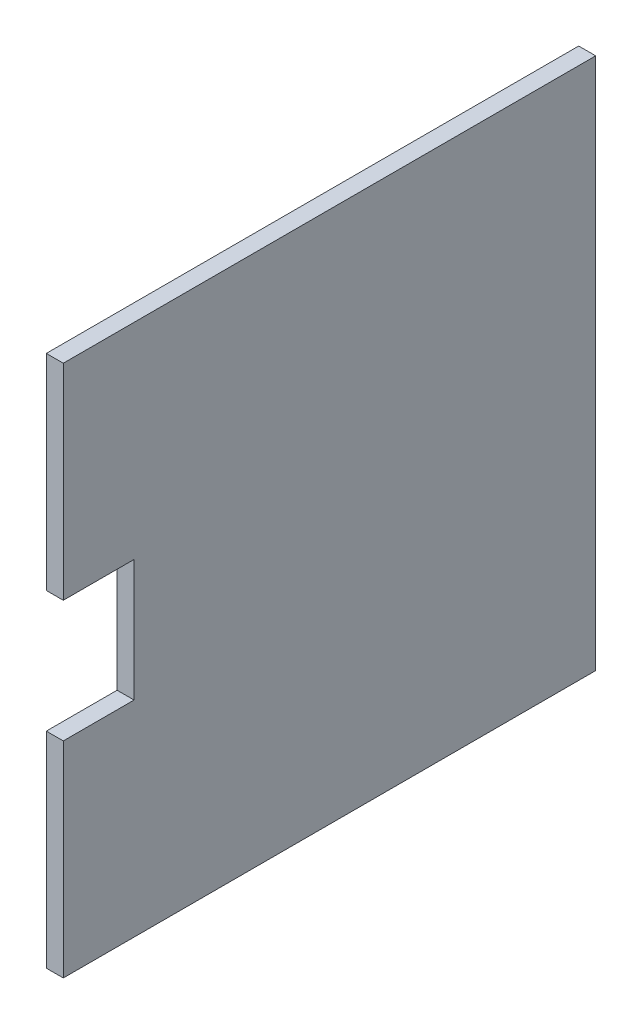
SolidWorks part; units mm, degrees
ref_plane "Front Plane" through (0, 0, 0) normal (0, 0, 1) x (1, 0, 0)
ref_plane "Top Plane" through (0, 0, 0) normal (0, 1, 0) x (1, 0, 0)
ref_plane "Right Plane" through (0, 0, 0) normal (1, 0, 0) x (0, 0, -1)
sketch "Sketch1" plane through (0, 0, 0) normal (1, 0, 0) x (0, 0, -1)
  line L0 (-81.0303, -37.5907) -> (-81.0303, -110.0907)
  line L1 (-81.0303, 77.9093) -> (106.9697, 77.9093)
  line L2 (-81.0303, 77.9093) -> (-81.0303, 5.4093)
  line L3 (-81.0303, -110.0907) -> (106.9697, -110.0907)
  line L4 (106.9697, 77.9093) -> (106.9697, -110.0907)
  line L7 (-81.0303, 5.4093) -> (-56.0303, 5.4093)
  line L8 (-56.0303, -16.0907) -> (-56.0303, 5.4093)
  line L11 (-81.0303, -37.5907) -> (-56.0303, -37.5907)
  line L12 (-56.0303, -16.0907) -> (-56.0303, -37.5907)
  dimension "D1" = 188
  dimension "D2" = 188
  dimension "D3" = 25
  dimension "D4" = 43
extrude "Boss-Extrude1" add sketch "Sketch1" along normal blind 6
